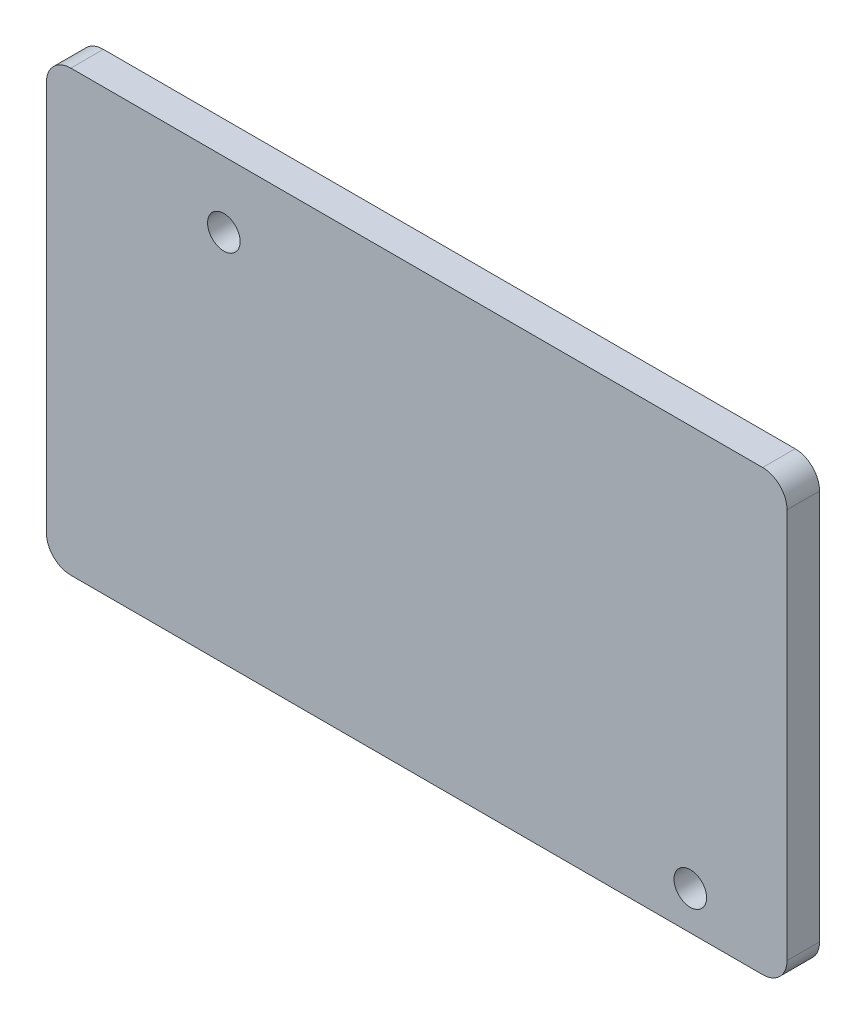
SolidWorks part; units mm, degrees
ref_plane "Front Plane" through (0, 0, 0) normal (0, 0, 1) x (1, 0, 0)
ref_plane "Top Plane" through (0, 0, 0) normal (0, 1, 0) x (1, 0, 0)
ref_plane "Right Plane" through (0, 0, 0) normal (1, 0, 0) x (0, 0, -1)
other "Mesh1"
other "Imported Mesh-1"
other "Imported Mesh-2"
other "Imported Mesh-3"
other "Imported Mesh-4"
other "Imported Mesh-5"
other "Imported Mesh-6"
other "Imported Mesh-7"
other "Imported Mesh-8"
other "Imported Mesh-9"
other "Imported Mesh-10"
other "Imported Mesh-11"
other "Imported Mesh-12"
other "Imported Mesh-13"
other "Imported Mesh-14"
other "Imported Mesh-15"
other "Imported Mesh-16"
other "Imported Mesh-17"
other "Imported Mesh-18"
other "Imported Mesh-19"
other "Imported Mesh-20"
other "Imported Mesh-21"
other "Imported Mesh-22"
other "Imported Mesh-23"
other "Imported Mesh-24"
other "Imported Mesh-25"
other "Imported Mesh-26"
other "Imported Mesh-27"
other "Imported Mesh-28"
other "Imported Mesh-29"
other "Imported Mesh-30"
other "Imported Mesh-31"
other "Imported Mesh-32"
other "Imported Mesh-33"
other "Imported Mesh-34"
other "Imported Mesh-35"
other "Imported Mesh-36"
other "Imported Mesh-37"
other "Imported Mesh-38"
other "Imported Mesh-39"
other "Imported Mesh-40"
other "Imported Mesh-41"
other "Imported Mesh-42"
other "Imported Mesh-43"
other "Imported Mesh-44"
other "Imported Mesh-45"
other "Imported Mesh-46"
other "Imported Mesh-47"
other "Imported Mesh-48"
other "Imported Mesh-49"
other "Imported Mesh-50"
other "Imported Mesh-51"
other "Imported Mesh-52"
other "Imported Mesh-53"
other "Imported Mesh-54"
other "Imported Mesh-55"
other "Imported Mesh-56"
other "Imported Mesh-57"
other "Imported Mesh-58"
other "Imported Mesh-59"
other "Imported Mesh-60"
other "Imported Mesh-61"
other "Imported Mesh-62"
other "Imported Mesh-63"
other "Imported Mesh-64"
other "Imported Mesh-65"
other "Imported Mesh-66"
other "Imported Mesh-67"
other "Imported Mesh-68"
other "Imported Mesh-69"
other "Imported Mesh-70"
other "Imported Mesh-71"
other "Imported Mesh-72"
other "Imported Mesh-73"
other "Imported Mesh-74"
other "Imported Mesh-75"
other "Imported Mesh-76"
other "Imported Mesh-77"
other "Imported Mesh-78"
other "Imported Mesh-79"
other "Imported Mesh-80"
other "Imported Mesh-81"
other "Imported Mesh-82"
other "Imported Mesh-83"
other "Imported Mesh-84"
other "Imported Mesh-85"
other "Imported Mesh-86"
other "Imported Mesh-87"
other "Imported Mesh-88"
other "Imported Mesh-89"
other "Imported Mesh-90"
other "Imported Mesh-91"
other "Imported Mesh-92"
other "Imported Mesh-93"
other "Imported Mesh-94"
other "Imported Mesh-95"
other "Imported Mesh-96"
sketch "Sketch1" plane through (0, 0, 0) normal (0, 0, 1) x (1, 0, 0)
  line L1 (-45.5054, 11.9326) -> (-2.9597, 11.9326)
  line L2 (-47.0054, 13.4326) -> (-47.0054, 37.4432)
  line L3 (-45.5054, 38.9432) -> (-2.9597, 38.9432)
  line L4 (-1.4597, 13.4326) -> (-1.4597, 37.4432)
  line L5 (-47.0054, 11.9326) -> (-1.4597, 38.9432) construction
  line L6 (-47.0054, 38.9432) -> (-1.4597, 11.9326) construction
  arc A0 (-1.4597, 37.4432) -> (-2.9597, 38.9432) centre (-2.9597, 37.4432) ccw
  arc A1 (-1.4597, 13.4326) -> (-2.9597, 11.9326) centre (-2.9597, 13.4326) cw
  arc A2 (-45.5054, 11.9326) -> (-47.0054, 13.4326) centre (-45.5054, 13.4326) cw
  arc A3 (-47.0054, 37.4432) -> (-45.5054, 38.9432) centre (-45.5054, 37.4432) cw
  circle A4 centre (-36.0943, 34.9052) radius 1.0022
  circle A5 centre (-7.4102, 14.2984) radius 1.0022
  point P0 (-24.2325, 25.4379)
  dimension "D1" = 1.5
  dimension "D2" = 2.0044
extrude "Boss-Extrude1" add sketch "Sketch1" against normal blind 2
